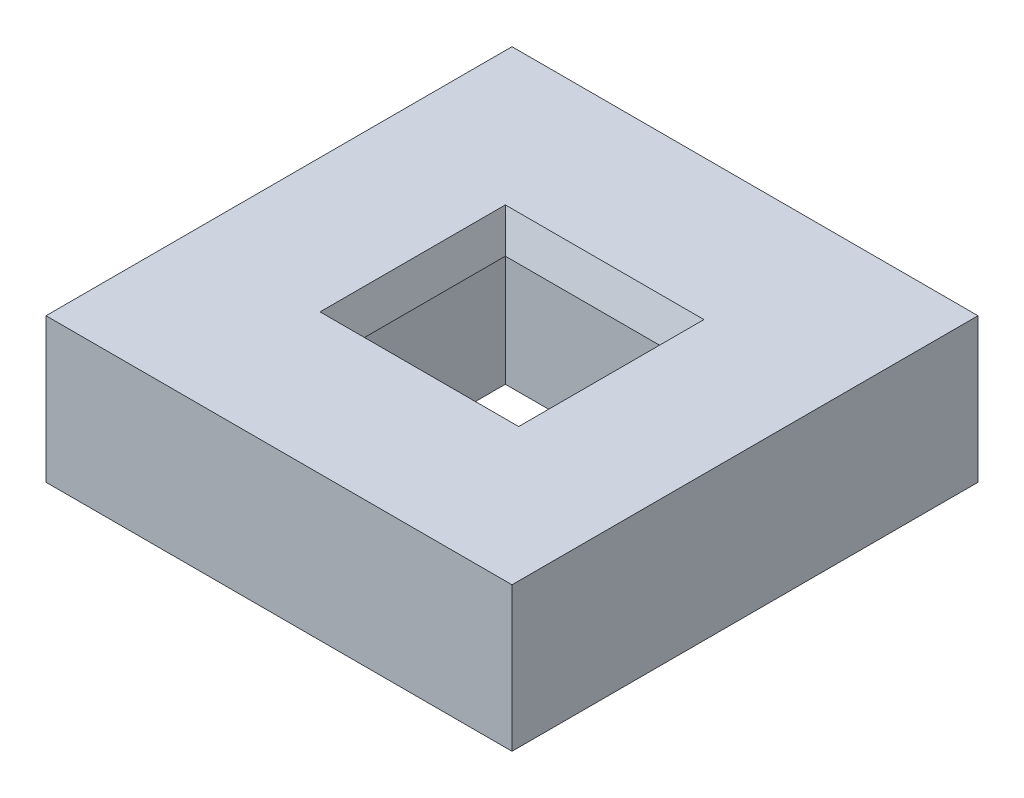
SolidWorks part; units mm, degrees
ref_plane "Front Plane" through (0, 0, 0) normal (0, 0, 1) x (1, 0, 0)
ref_plane "Top Plane" through (0, 0, 0) normal (0, 1, 0) x (1, 0, 0)
ref_plane "Right Plane" through (0, 0, 0) normal (1, 0, 0) x (0, 0, -1)
sketch "Sketch1" plane through (0, 0, 0) normal (0, 1, 0) x (1, 0, 0)
  line L1 (-3.975, 3.675) -> (3.975, 3.675)
  line L2 (-3.975, 3.675) -> (-3.975, -3.675)
  line L3 (-3.975, -3.675) -> (3.975, -3.675)
  line L4 (3.975, 3.675) -> (3.975, -3.675)
  line L5 (-10.5, 10.5) -> (10.5, 10.5)
  line L6 (-10.5, 10.5) -> (-10.5, -10.5)
  line L7 (-10.5, -10.5) -> (10.5, -10.5)
  line L8 (10.5, 10.5) -> (10.5, -10.5)
  point P8 (0, 3.675)
  point P10 (0, 10.5)
  point P11 (-3.975, 0)
  point P12 (-10.5, 0)
  dimension "D1" = 7.95
  dimension "D2" = 21
  dimension "D3" = 7.35
extrude "Boss-Extrude1" add sketch "Sketch1" along normal blind 6.5
chamfer "Chamfer1" distance 0.5 distance2 1.5 4 edges at (3.975, 6.5, 0) (0, 6.5, 3.675) (-3.975, 6.5, 0) (0, 6.5, -3.675)
